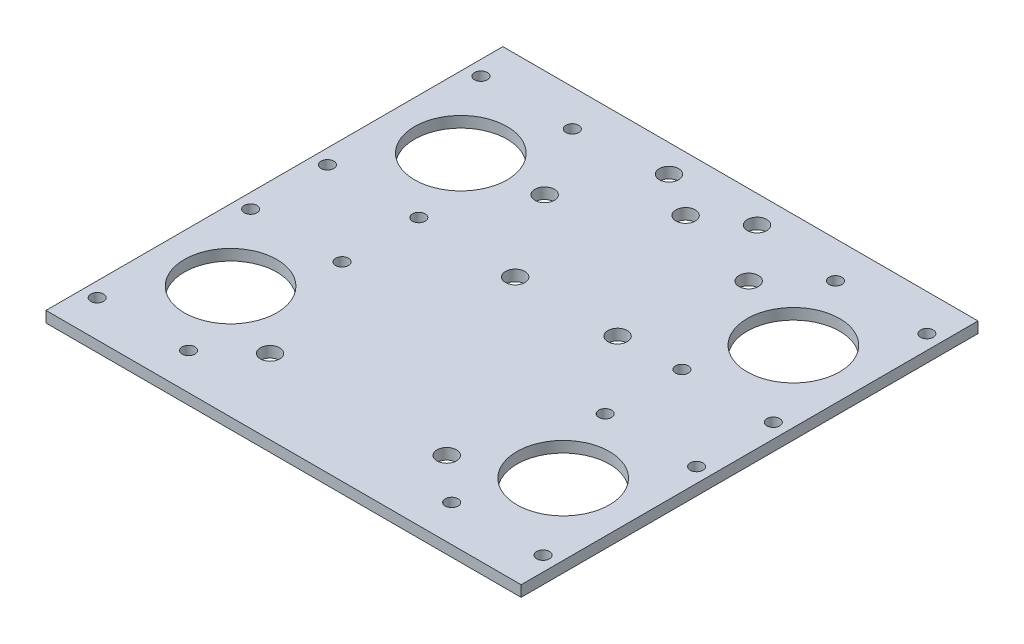
SolidWorks part; units mm, degrees
ref_plane "Front Plane" through (0, 0, 0) normal (0, 0, 1) x (1, 0, 0)
ref_plane "Top Plane" through (0, 0, 0) normal (0, 1, 0) x (1, 0, 0)
ref_plane "Right Plane" through (0, 0, 0) normal (1, 0, 0) x (0, 0, -1)
sketch "Sketch1" plane through (0, 0, 0) normal (0, 1, 0) x (1, 0, 0)
  line L1 (-65, 62.5) -> (65, 62.5)
  line L2 (-65, 62.5) -> (-65, -62.5)
  line L3 (-65, -62.5) -> (65, -62.5)
  line L4 (65, 62.5) -> (65, -62.5)
  line L5 (-65, 62.5) -> (65, -62.5) construction
  line L6 (-65, -62.5) -> (65, 62.5) construction
  point P0 (0, 0)
  dimension "D1" = 130
  dimension "D2" = 125
extrude "Boss-Extrude1" add sketch "Sketch1" along normal blind 3
sketch "Sketch2" plane through (0, 3, 0) normal (0, 1, 0) x (1, 0, 0)
  line L1 (-65, -62.5) -> (65, -62.5) construction
  line L2 (-65, 62.5) -> (-65, -62.5) construction
  circle A0 centre (-61, -52.5) radius 1.75
  circle A1 centre (-36, -52.5) radius 1.75
  circle A2 centre (-36, -10.5) radius 1.75
  circle A3 centre (-61, -10.5) radius 1.75
  circle A4 centre (-45.5, -31.5) radius 12.65
  point P14 (0, 0)
  point P15 (0, 0)
  dimension "D2" = 25.3
  dimension "D7" = 3.5
  dimension "D8" = 3.5
  dimension "D9" = 3.5
  dimension "D10" = 3.5
  dimension "D1" = 19.5
  dimension "D3" = 31
  dimension "D4" = 4
  dimension "D5" = 10
  dimension "D6" = 10
  dimension "D11" = 4
  dimension "D12" = 42
  dimension "D13" = 42
  dimension "D14" = 25
  dimension "D15" = 25
extrude "Cut-Extrude1" cut sketch "Sketch2" against normal blind 10
ref_plane "Plane1" through (0, 0, 0) normal (-1, 0, 0) x (0, 0, 1)
ref_plane "Plane2" through (0, 0, 0) normal (0, 0, 1) x (1, 0, 0)
mirror "Mirror3" about plane through (0, 0, 0) normal (-1, 0, 0) of "Cut-Extrude1"
mirror "Mirror4" about plane through (0, 0, 0) normal (0, 0, 1) of "Mirror3", "Cut-Extrude1"
sketch "Sketch3" plane through (0, 3, 0) normal (0, 1, 0) x (1, 0, 0)
  line L0 (-65, -62.5) -> (65, -62.5) construction
  line L1 (-65, 62.5) -> (-65, -62.5) construction
  line L2 (65, -62.5) -> (65, 62.5) construction
  line L3 (65, 62.5) -> (-65, 62.5) construction
  circle A0 centre (-24.17, -42.03) radius 2.65
  circle A1 centre (24.17, -42.03) radius 2.65
  circle A2 centre (-8.73, 9.6) radius 2.65
  circle A3 centre (19.29, 9.6) radius 2.65
  circle A4 centre (-24.17, 33.11) radius 2.65
  circle A5 centre (24.17, 40.6) radius 2.65
  dimension "D1" = 5.3
  dimension "D6" = 5.3
  dimension "D7" = 5.3
  dimension "D10" = 5.3
  dimension "D11" = 5.3
  dimension "D12" = 5.3
  dimension "D2" = 20.47
  dimension "D3" = 40.83
  dimension "D4" = 20.47
  dimension "D5" = 40.83
  dimension "D8" = 72.1
  dimension "D9" = 56.27
  dimension "D13" = 45.71
  dimension "D14" = 72.1
  dimension "D15" = 29.39
  dimension "D16" = 21.9
  dimension "D17" = 40.83
extrude "Cut-Extrude2" cut sketch "Sketch3" against normal blind 10
sketch "Sketch4" plane through (0, 3, 0) normal (0, 1, 0) x (1, 0, 0)
  line L0 (0, 62.5) -> (0, 47.5) construction
  line L1 (65, 62.5) -> (-65, 62.5) construction
  line L2 (-12.0498, 55) -> (12.0498, 55) construction
  circle A0 centre (0, 47.5) radius 2.65
  circle A1 centre (12.0498, 55) radius 2.65
  circle A2 centre (-12.0498, 55) radius 2.65
  point P9 (0, 55)
  point P11 (0, 0)
  dimension "D2" = 5.3
  dimension "D3" = 5.3
  dimension "D4" = 5.3
  dimension "D1" = 15
extrude "Cut-Extrude3" cut sketch "Sketch4" against normal blind 10
